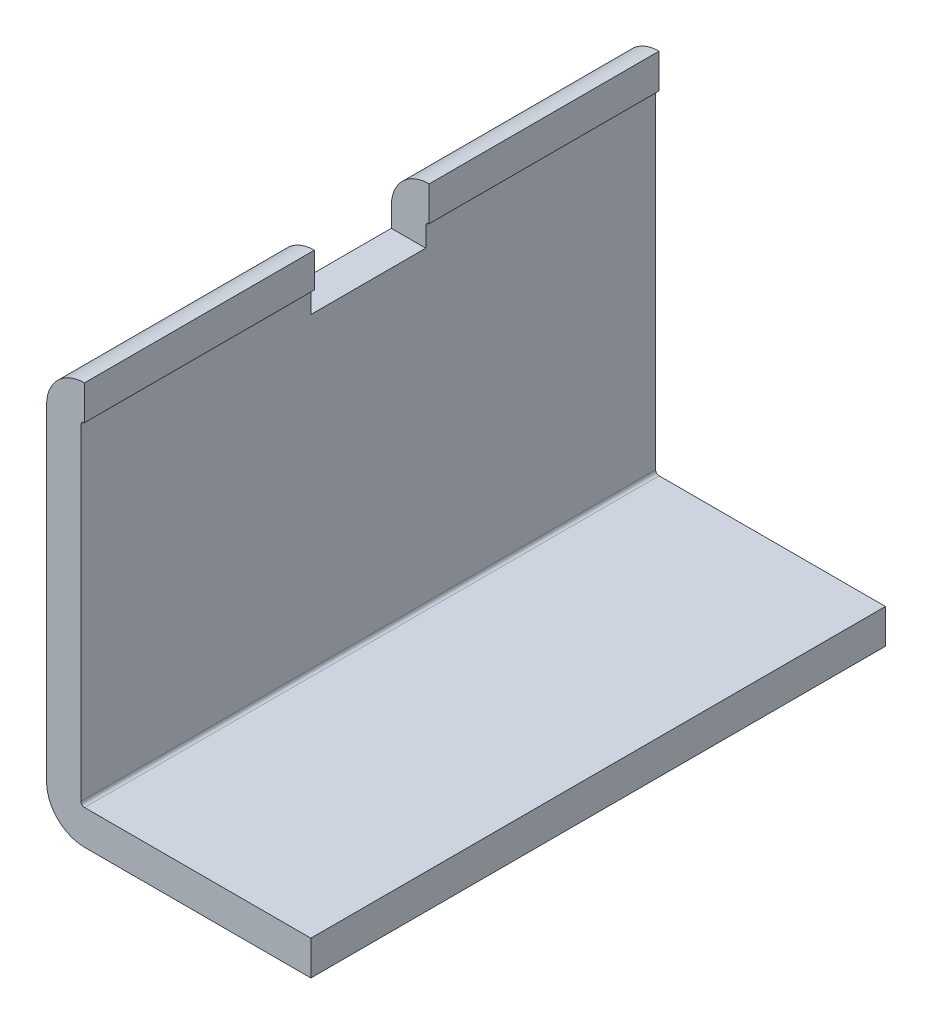
SolidWorks part; units mm, degrees
ref_plane "前视基准面" through (0, 0, 0) normal (0, 0, 1) x (1, 0, 0)
ref_plane "上视基准面" through (0, 0, 0) normal (0, 1, 0) x (1, 0, 0)
ref_plane "右视基准面" through (0, 0, 0) normal (1, 0, 0) x (0, 0, -1)
sketch "草图1" plane through (0, 0, 0) normal (0, 0, 1) x (1, 0, 0)
  line L1 (0, 0) -> (0, -2.84)
  line L2 (0.03, -2.87) -> (2, -2.87)
  arc A0 (0, 0) -> (0.03, 0.03) centre (0.03, 0) cw
  arc A1 (0, -2.84) -> (0.03, -2.87) centre (0.03, -2.84) ccw
  point P6 (0, -2.87)
  dimension "D3" = 0.03
  dimension "D4" = 0.03
  dimension "D2" = 2
  dimension "D1" = 2.9
extrude "拉伸-薄壁1" add sketch "草图1" along normal blind 5 thin
sketch "草图2" plane through (0.03, 0, 0) normal (1, 0, 0) x (0, 0, -1)
  line L0 (-2.5, 0.33) -> (-2.5, 0.03) construction
  line L1 (-5, 0.33) -> (0, 0.33) construction
  line L2 (-5, 0.03) -> (0, 0.03) construction
  line L4 (-2, -0.17) -> (-3, -0.17)
  line L5 (-2, -0.17) -> (-2, 0.33)
  line L6 (-2, 0.33) -> (-3, 0.33)
  line L7 (-3, -0.17) -> (-3, 0.33)
  line L8 (-2, -0.17) -> (-3, 0.33) construction
  line L9 (-2, 0.33) -> (-3, -0.17) construction
  point P6 (-2.5, 0.08)
  dimension "D1" = 1
  dimension "D2" = 0.5
extrude "切除-拉伸1" cut sketch "草图2" against normal through all both and the other way through all
equation "\"A\"= 12.6mm'宽度"
equation "\"B\"= 13.45mm'长度"
equation "\"C\"= 5.8mm'高度"
equation "\"D\"= 2.0mm'引脚宽度"
equation "\"E\"= 5.0mm'引脚长度"
equation "\"F\"= 0.3mm'引脚厚度"
equation "\"D2@草图1\"=\"D\""
equation "\"D3@草图1\"=0.1*\"F\""
equation "\"D4@草图1\"=0.1*\"F\""
equation "\"D5@拉伸-薄壁1\"=\"F\""
equation "\"D1@拉伸-薄壁1\"=\"E\""
equation "\"D1@草图2\"=0.2*\"E\""
equation "\"D2@草图2\"=0.1*\"E\""
equation "\"D1@圆角1\"=0.2*\"F\""
equation "\"D1@草图1\"=0.5*\"C\""
